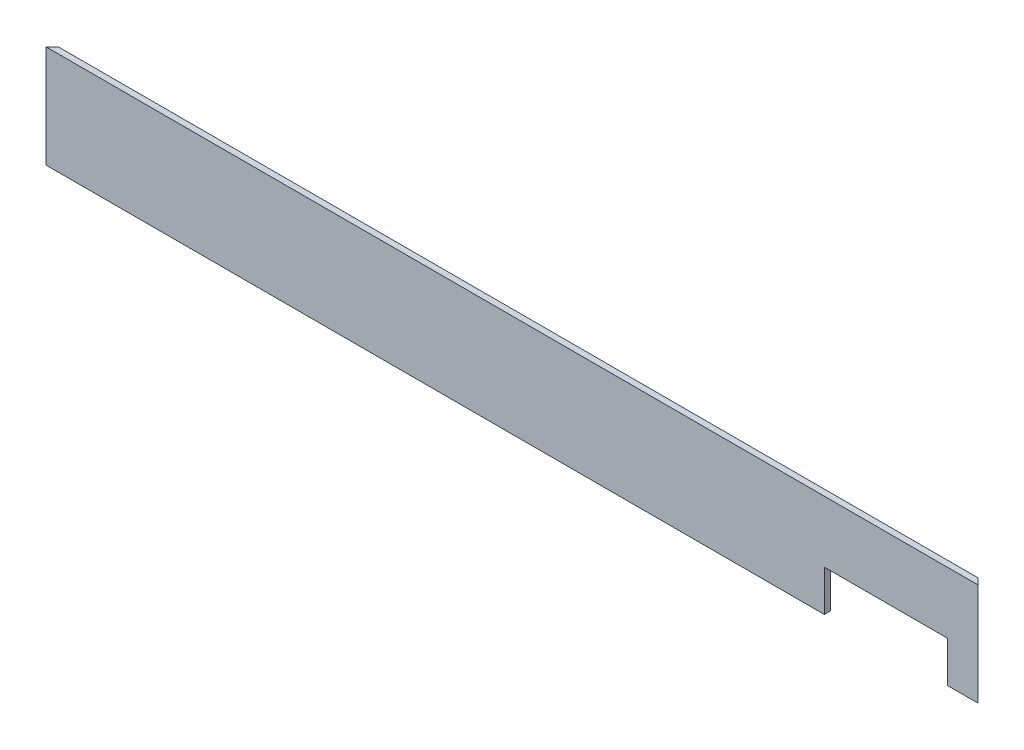
SolidWorks part; units mm, degrees
ref_plane "Front Plane" through (0, 0, 0) normal (0, 0, 1) x (1, 0, 0)
ref_plane "Top Plane" through (0, 0, 0) normal (0, 1, 0) x (1, 0, 0)
ref_plane "Right Plane" through (0, 0, 0) normal (1, 0, 0) x (0, 0, -1)
sketch "Sketch1" plane through (0, 0, 0) normal (0, 1, 0) x (1, 0, 0)
  line L1 (227.5, -1.5) -> (-227.5, -1.5)
  line L2 (227.5, -1.5) -> (227.5, 1.5)
  line L3 (227.5, 1.5) -> (-227.5, 1.5)
  line L4 (-227.5, -1.5) -> (-227.5, 1.5)
  line L5 (227.5, -1.5) -> (-227.5, 1.5) construction
  line L6 (227.5, 1.5) -> (-227.5, -1.5) construction
  point P0 (0, 0)
  dimension "D1" = 455
  dimension "D2" = 3
extrude "Boss-Extrude1" add sketch "Sketch1" along normal blind 50
sketch "Sketch2" plane through (0, 0, 1.5) normal (0, 0, 1) x (1, 0, 0)
  line L0 (-227.5, 0) -> (227.5, 0) construction
  line L1 (212.5, 0) -> (152.5, 0)
  line L2 (212.5, 0) -> (212.5, 20)
  line L3 (212.5, 20) -> (152.5, 20)
  line L4 (152.5, 0) -> (152.5, 20)
  line L5 (212.5, 0) -> (152.5, 20) construction
  line L6 (212.5, 20) -> (152.5, 0) construction
  line L7 (227.5, 50) -> (227.5, 0) construction
  point P0 (182.5, 10)
  dimension "D1" = 60
  dimension "D2" = 20
  dimension "D3" = 0
  dimension "D4" = 15
extrude "Cut-Extrude1" cut sketch "Sketch2" against normal blind 55
sketch "Sketch3" plane through (0, 50, 0) normal (0, 1, 0) x (1, 0, 0)
  line L0 (-227.5, 1.5) -> (-227.5, -1.5)
  line L2 (-227.5, 1.5) -> (-224.5, 1.5)
  line L3 (227.5, 1.5) -> (-227.5, 1.5) construction
  line L4 (-227.5, -1.5) -> (-224.5, 1.5)
  line L5 (227.5, 1.5) -> (227.5, -1.5)
  line L7 (227.5, -1.5) -> (224.5, 1.5)
  line L8 (224.5, 1.5) -> (227.5, 1.5)
  dimension "D1" = 45
  dimension "D2" = 45
extrude "Cut-Extrude2" cut sketch "Sketch3" against normal through all
